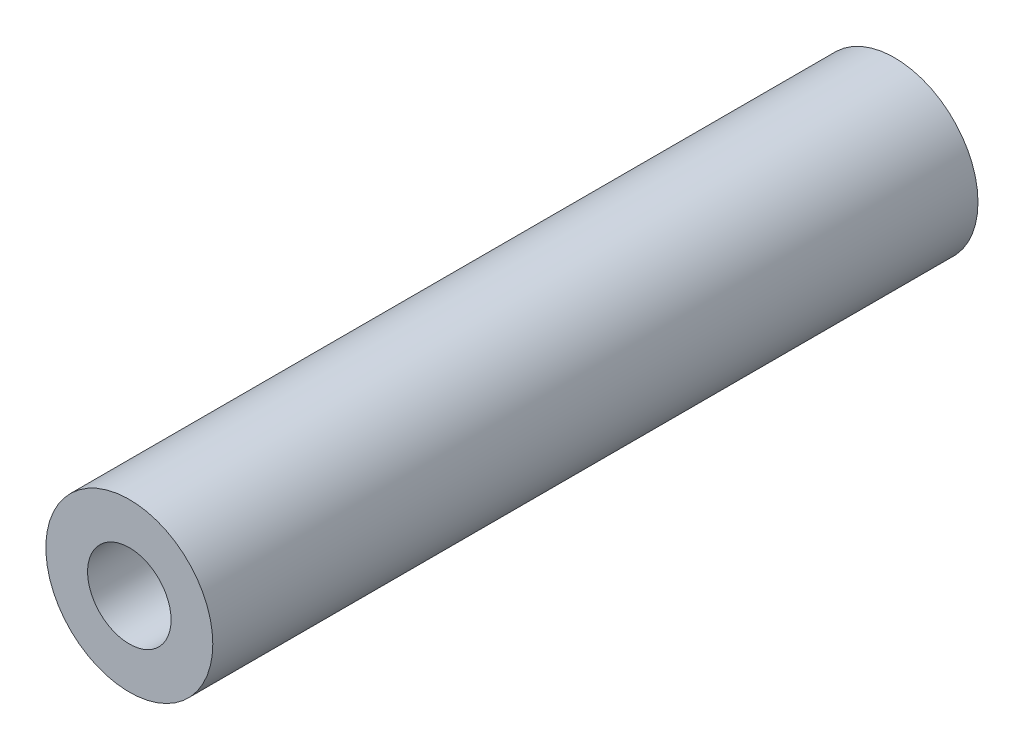
SolidWorks part; units mm, degrees
material "Cast Alloy Steel"
ref_plane "Front Plane" through (0, 0, 0) normal (0, 0, 1) x (1, 0, 0)
ref_plane "Top Plane" through (0, 0, 0) normal (0, 1, 0) x (1, 0, 0)
ref_plane "Right Plane" through (0, 0, 0) normal (1, 0, 0) x (0, 0, -1)
sketch "Sketch1" plane through (0, 0, 0) normal (0, 0, 1) x (1, 0, 0)
  circle A0 centre (0, 0) radius 6
  circle A1 centre (0, 0) radius 3
  dimension "D1" = 12
  dimension "D2" = 6
extrude "Boss-Extrude1" add sketch "Sketch1" along normal blind 55
